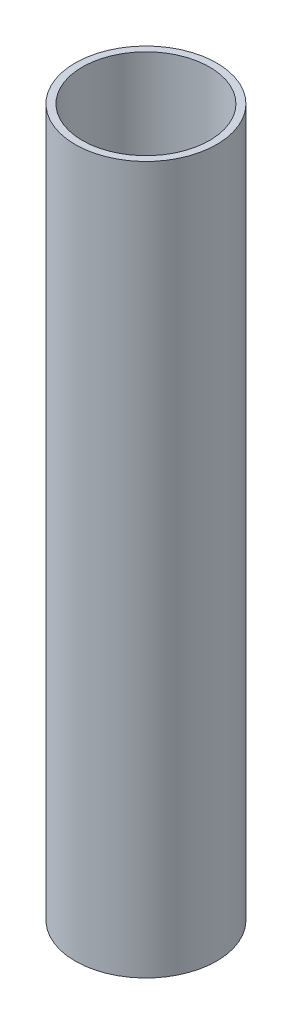
SolidWorks part; units mm, degrees
ref_plane "前视基准面" through (0, 0, 0) normal (0, 0, 1) x (1, 0, 0)
ref_plane "上视基准面" through (0, 0, 0) normal (0, 1, 0) x (1, 0, 0)
ref_plane "右视基准面" through (0, 0, 0) normal (1, 0, 0) x (0, 0, -1)
sketch "草图1" plane through (0, 0, 0) normal (0, 1, 0) x (1, 0, 0)
  circle A0 centre (-19.3896, 19.8744) radius 5
extrude "凸台-拉伸1" add sketch "草图1" along normal blind 50
sketch "草图3" plane through (0, 0, 0) normal (0, 1, 0) x (1, 0, 0)
  circle A0 centre (-19.3896, 19.8744) radius 4.5
extrude "切除-拉伸1" cut sketch "草图3" along normal through all
